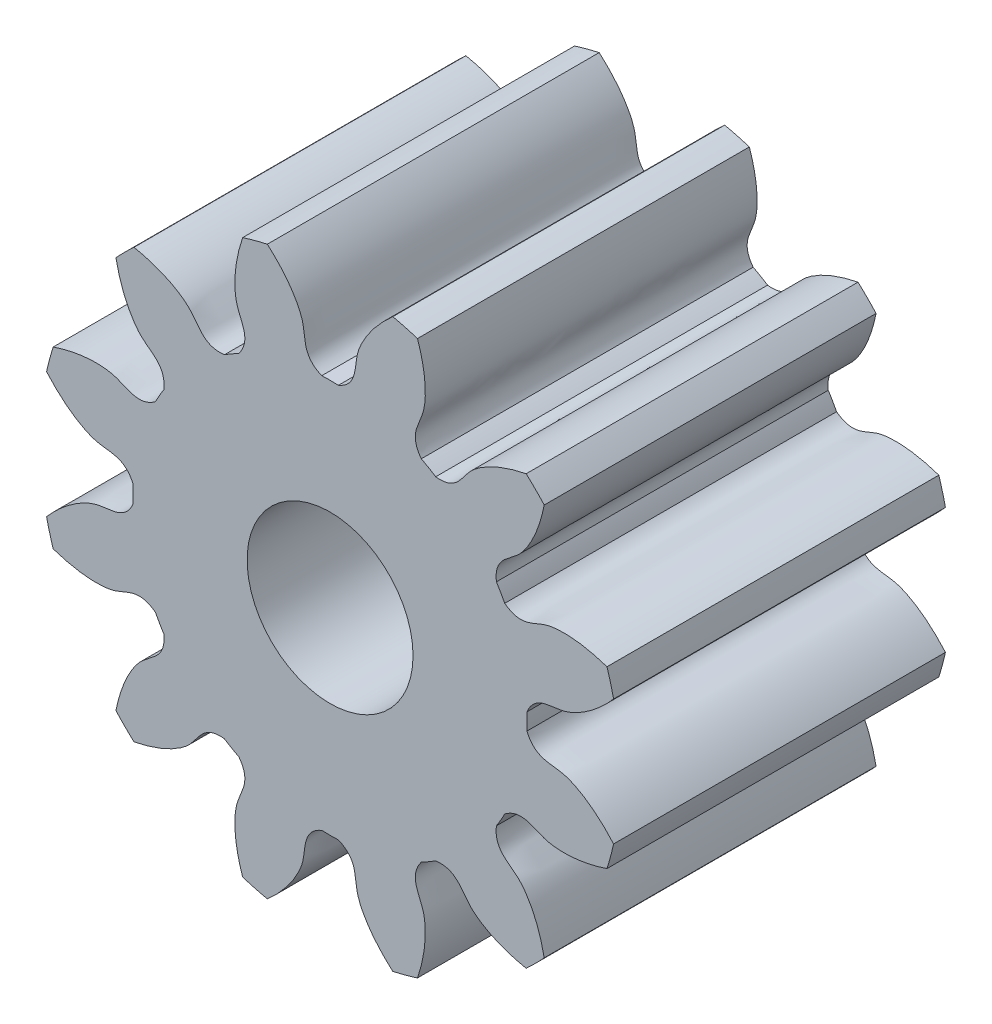
SolidWorks part; units mm, degrees
ref_plane "前视基准面" through (0, 0, 0) normal (0, 0, 1) x (1, 0, 0)
ref_plane "上视基准面" through (0, 0, 0) normal (0, 1, 0) x (1, 0, 0)
ref_plane "右视基准面" through (0, 0, 0) normal (1, 0, 0) x (0, 0, -1)
sketch "草图1" plane through (0, 0, 0) normal (0, 0, 1) x (1, 0, 0)
  arc A0 (-264.4461, -183.3216) -> (-265.0406, -183.4809) centre (-262.9333, -190.1562) ccw
  arc A1 (-262.7325, -185.4104) -> (-263.1342, -185.4104) centre (-262.9333, -190.1562) ccw
  arc A2 (-260.8261, -183.4809) -> (-261.4206, -183.3216) centre (-262.9333, -190.1562) ccw
  arc A3 (-260.3865, -186.1467) -> (-260.7344, -185.9458) centre (-262.9333, -190.1562) ccw
  arc A4 (-257.7708, -185.4288) -> (-258.206, -184.9936) centre (-262.9333, -190.1562) ccw
  arc A5 (-258.723, -187.9572) -> (-258.9238, -187.6094) centre (-262.9333, -190.1562) ccw
  arc A6 (-256.0987, -188.6434) -> (-256.258, -188.0489) centre (-262.9333, -190.1562) ccw
  arc A7 (-258.1876, -190.357) -> (-258.1876, -189.9553) centre (-262.9333, -190.1562) ccw
  arc A8 (-256.258, -192.2634) -> (-256.0987, -191.6689) centre (-262.9333, -190.1562) ccw
  arc A9 (-258.9238, -192.703) -> (-258.723, -192.3551) centre (-262.9333, -190.1562) ccw
  arc A10 (-258.206, -195.3187) -> (-257.7708, -194.8835) centre (-262.9333, -190.1562) ccw
  arc A11 (-260.7344, -194.3665) -> (-260.3865, -194.1657) centre (-262.9333, -190.1562) ccw
  arc A12 (-261.4206, -196.9908) -> (-260.8261, -196.8315) centre (-262.9333, -190.1562) ccw
  arc A13 (-263.1342, -194.9019) -> (-262.7325, -194.9019) centre (-262.9333, -190.1562) ccw
  arc A14 (-265.0406, -196.8315) -> (-264.4461, -196.9908) centre (-262.9333, -190.1562) ccw
  arc A15 (-265.4801, -194.1657) -> (-265.1323, -194.3665) centre (-262.9333, -190.1562) ccw
  arc A16 (-268.0959, -194.8835) -> (-267.6607, -195.3187) centre (-262.9333, -190.1562) ccw
  arc A17 (-267.1437, -192.3551) -> (-266.9429, -192.703) centre (-262.9333, -190.1562) ccw
  arc A18 (-269.7679, -191.6689) -> (-269.6086, -192.2634) centre (-262.9333, -190.1562) ccw
  arc A19 (-267.6791, -189.9553) -> (-267.6791, -190.357) centre (-262.9333, -190.1562) ccw
  arc A20 (-269.6086, -188.0489) -> (-269.7679, -188.6434) centre (-262.9333, -190.1562) ccw
  arc A21 (-266.9429, -187.6094) -> (-267.1437, -187.9572) centre (-262.9333, -190.1562) ccw
  arc A22 (-267.6607, -184.9936) -> (-268.0959, -185.4288) centre (-262.9333, -190.1562) ccw
  arc A23 (-265.1323, -185.9458) -> (-265.4801, -186.1467) centre (-262.9333, -190.1562) ccw
  circle A24 centre (-262.9333, -190.1562) radius 2
  spline S0 degree 3 poles (-265.1323, -185.9458) (-264.8184, -185.5296) (-265.1083, -185.2402) (-265.1944, -184.8832) (-265.2024, -184.8445) (-265.2113, -184.7911) (-265.2193, -184.7285) (-265.2255, -184.6566) (-265.2292, -184.5755) (-265.2298, -184.4852) (-265.2264, -184.386) (-265.2185, -184.2781) (-265.2052, -184.1615) (-265.1822, -184.0133) (-265.1444, -183.8306) (-265.0941, -183.6446) (-265.0562, -183.5266) (-265.0406, -183.4809) knots 0 0 0 0 0.218015 0.222044 0.231522 0.242897 0.256167 0.271332 0.288394 0.307351 0.328204 0.350953 0.375597 0.402137 0.445502 0.493132 0.523596 0.523596 0.523596 0.523596
  spline S1 degree 3 poles (-264.4461, -183.3216) (-264.3902, -183.3705) (-264.2991, -183.4545) (-264.1796, -183.5761) (-264.0856, -183.6797) (-264.0016, -183.78) (-263.9272, -183.8764) (-263.8619, -183.9684) (-263.8053, -184.0554) (-263.7568, -184.1367) (-263.7159, -184.2121) (-263.682, -184.2809) (-263.6546, -184.3427) (-263.6329, -184.3972) (-263.6186, -184.438) (-263.6095, -184.4667) (-263.5077, -184.8114) (-263.6141, -185.2069) (-263.1342, -185.4104) knots 0.476404 0.476404 0.476404 0.476404 0.523219 0.554498 0.583882 0.61137 0.636962 0.660659 0.682459 0.702364 0.720374 0.736487 0.750705 0.763028 0.773454 0.777956 0.781985 1 1 1 1
  spline S2 degree 3 poles (-262.7325, -185.4104) (-262.2525, -185.2069) (-262.359, -184.8114) (-262.2549, -184.4591) (-262.2426, -184.4216) (-262.2236, -184.3709) (-262.1992, -184.3127) (-262.1686, -184.2473) (-262.1312, -184.1752) (-262.0866, -184.0968) (-262.0341, -184.0125) (-261.9732, -183.923) (-261.9035, -183.8287) (-261.8095, -183.7118) (-261.6854, -183.5726) (-261.5488, -183.4366) (-261.457, -183.3534) (-261.4206, -183.3216) knots 0 0 0 0 0.218015 0.222044 0.231522 0.242897 0.256167 0.271332 0.288394 0.307351 0.328204 0.350953 0.375597 0.402137 0.445502 0.493132 0.523596 0.523596 0.523596 0.523596
  spline S3 degree 3 poles (-260.8261, -183.4809) (-260.8021, -183.5512) (-260.7653, -183.6695) (-260.7226, -183.8346) (-260.6929, -183.9712) (-260.6704, -184.1001) (-260.6541, -184.2208) (-260.6436, -184.3331) (-260.638, -184.4367) (-260.6367, -184.5315) (-260.639, -184.6172) (-260.6441, -184.6937) (-260.6512, -184.761) (-260.6597, -184.819) (-260.6677, -184.8615) (-260.6742, -184.8909) (-260.7583, -185.2402) (-261.0483, -185.5296) (-260.7344, -185.9458) knots 0.476404 0.476404 0.476404 0.476404 0.523219 0.554498 0.583882 0.61137 0.636962 0.660659 0.682459 0.702364 0.720374 0.736487 0.750705 0.763028 0.773454 0.777956 0.781985 1 1 1 1
  spline S4 degree 3 poles (-260.3865, -186.1467) (-259.8691, -186.2103) (-259.7635, -185.8146) (-259.4973, -185.5616) (-259.4679, -185.5353) (-259.4261, -185.5009) (-259.3758, -185.4627) (-259.3166, -185.4213) (-259.2482, -185.3775) (-259.1704, -185.3319) (-259.0828, -185.2852) (-258.9853, -185.2381) (-258.8777, -185.1914) (-258.7379, -185.1371) (-258.5608, -185.0786) (-258.3745, -185.0291) (-258.2534, -185.003) (-258.206, -184.9936) knots 0 0 0 0 0.218015 0.222044 0.231522 0.242897 0.256167 0.271332 0.288394 0.307351 0.328204 0.350953 0.375597 0.402137 0.445502 0.493132 0.523596 0.523596 0.523596 0.523596
  spline S5 degree 3 poles (-257.7708, -185.4288) (-257.7852, -185.5017) (-257.8124, -185.6226) (-257.8579, -185.7869) (-257.9006, -185.9201) (-257.9455, -186.043) (-257.9918, -186.1556) (-258.0388, -186.2581) (-258.0858, -186.3506) (-258.1321, -186.4333) (-258.1769, -186.5064) (-258.2195, -186.5702) (-258.2594, -186.6249) (-258.2957, -186.6709) (-258.3239, -186.7037) (-258.3442, -186.7259) (-258.5918, -186.9863) (-258.9875, -187.0919) (-258.9238, -187.6094) knots 0.476404 0.476404 0.476404 0.476404 0.523219 0.554498 0.583882 0.61137 0.636962 0.660659 0.682459 0.702364 0.720374 0.736487 0.750705 0.763028 0.773454 0.777956 0.781985 1 1 1 1
  spline S6 degree 3 poles (-258.723, -187.9572) (-258.3067, -188.2711) (-258.0174, -187.9812) (-257.6603, -187.8952) (-257.6217, -187.8871) (-257.5683, -187.8782) (-257.5056, -187.8703) (-257.4337, -187.8641) (-257.3526, -187.8603) (-257.2624, -187.8598) (-257.1632, -187.8631) (-257.0552, -187.8711) (-256.9387, -187.8843) (-256.7904, -187.9073) (-256.6078, -187.9451) (-256.4217, -187.9954) (-256.3038, -188.0334) (-256.258, -188.0489) knots 0 0 0 0 0.218015 0.222044 0.231522 0.242897 0.256167 0.271332 0.288394 0.307351 0.328204 0.350953 0.375597 0.402137 0.445502 0.493132 0.523596 0.523596 0.523596 0.523596
  spline S7 degree 3 poles (-256.0987, -188.6434) (-256.1476, -188.6993) (-256.2317, -188.7904) (-256.3533, -188.91) (-256.4568, -189.0039) (-256.5571, -189.0879) (-256.6536, -189.1623) (-256.7456, -189.2276) (-256.8325, -189.2842) (-256.9139, -189.3327) (-256.9892, -189.3736) (-257.058, -189.4075) (-257.1199, -189.435) (-257.1744, -189.4566) (-257.2152, -189.4709) (-257.2439, -189.48) (-257.5885, -189.5818) (-257.984, -189.4754) (-258.1876, -189.9553) knots 0.476404 0.476404 0.476404 0.476404 0.523219 0.554498 0.583882 0.61137 0.636962 0.660659 0.682459 0.702364 0.720374 0.736487 0.750705 0.763028 0.773454 0.777956 0.781985 1 1 1 1
  spline S8 degree 3 poles (-258.1876, -190.357) (-257.984, -190.837) (-257.5885, -190.7306) (-257.2363, -190.8346) (-257.1988, -190.8469) (-257.1481, -190.8659) (-257.0899, -190.8904) (-257.0245, -190.9209) (-256.9524, -190.9583) (-256.8739, -191.0029) (-256.7897, -191.0554) (-256.7002, -191.1163) (-256.6059, -191.186) (-256.489, -191.28) (-256.3497, -191.4041) (-256.2137, -191.5407) (-256.1306, -191.6325) (-256.0987, -191.6689) knots 0 0 0 0 0.218015 0.222044 0.231522 0.242897 0.256167 0.271332 0.288394 0.307351 0.328204 0.350953 0.375597 0.402137 0.445502 0.493132 0.523596 0.523596 0.523596 0.523596
  spline S9 degree 3 poles (-256.258, -192.2634) (-256.3283, -192.2874) (-256.4466, -192.3242) (-256.6117, -192.3669) (-256.7484, -192.3966) (-256.8773, -192.4191) (-256.998, -192.4354) (-257.1103, -192.4459) (-257.2139, -192.4515) (-257.3086, -192.4528) (-257.3943, -192.4505) (-257.4708, -192.4455) (-257.5381, -192.4383) (-257.5962, -192.4298) (-257.6387, -192.4218) (-257.668, -192.4154) (-258.0174, -192.3312) (-258.3067, -192.0413) (-258.723, -192.3551) knots 0.476404 0.476404 0.476404 0.476404 0.523219 0.554498 0.583882 0.61137 0.636962 0.660659 0.682459 0.702364 0.720374 0.736487 0.750705 0.763028 0.773454 0.777956 0.781985 1 1 1 1
  spline S10 degree 3 poles (-258.9238, -192.703) (-258.9875, -193.2204) (-258.5918, -193.326) (-258.3387, -193.5922) (-258.3124, -193.6216) (-258.278, -193.6634) (-258.2398, -193.7137) (-258.1985, -193.7729) (-258.1547, -193.8413) (-258.1091, -193.9192) (-258.0624, -194.0067) (-258.0153, -194.1042) (-257.9685, -194.2118) (-257.9143, -194.3516) (-257.8557, -194.5287) (-257.8063, -194.715) (-257.7801, -194.8361) (-257.7708, -194.8835) knots 0 0 0 0 0.218015 0.222044 0.231522 0.242897 0.256167 0.271332 0.288394 0.307351 0.328204 0.350953 0.375597 0.402137 0.445502 0.493132 0.523596 0.523596 0.523596 0.523596
  spline S11 degree 3 poles (-258.206, -195.3187) (-258.2788, -195.3044) (-258.3997, -195.2771) (-258.564, -195.2316) (-258.6972, -195.1889) (-258.8201, -195.144) (-258.9328, -195.0977) (-259.0353, -195.0507) (-259.1278, -195.0037) (-259.2105, -194.9574) (-259.2836, -194.9126) (-259.3473, -194.87) (-259.402, -194.8302) (-259.448, -194.7938) (-259.4808, -194.7656) (-259.503, -194.7453) (-259.7635, -194.4977) (-259.8691, -194.102) (-260.3865, -194.1657) knots 0.476404 0.476404 0.476404 0.476404 0.523219 0.554498 0.583882 0.61137 0.636962 0.660659 0.682459 0.702364 0.720374 0.736487 0.750705 0.763028 0.773454 0.777956 0.781985 1 1 1 1
  spline S12 degree 3 poles (-260.7344, -194.3665) (-261.0483, -194.7828) (-260.7583, -195.0721) (-260.6723, -195.4292) (-260.6643, -195.4678) (-260.6553, -195.5212) (-260.6474, -195.5839) (-260.6412, -195.6558) (-260.6375, -195.7369) (-260.6369, -195.8271) (-260.6402, -195.9263) (-260.6482, -196.0343) (-260.6615, -196.1508) (-260.6844, -196.2991) (-260.7223, -196.4817) (-260.7726, -196.6678) (-260.8105, -196.7857) (-260.8261, -196.8315) knots 0 0 0 0 0.218015 0.222044 0.231522 0.242897 0.256167 0.271332 0.288394 0.307351 0.328204 0.350953 0.375597 0.402137 0.445502 0.493132 0.523596 0.523596 0.523596 0.523596
  spline S13 degree 3 poles (-261.4206, -196.9908) (-261.4765, -196.9419) (-261.5676, -196.8578) (-261.6871, -196.7362) (-261.7811, -196.6327) (-261.8651, -196.5324) (-261.9395, -196.4359) (-262.0048, -196.3439) (-262.0614, -196.257) (-262.1099, -196.1756) (-262.1508, -196.1003) (-262.1847, -196.0315) (-262.2121, -195.9696) (-262.2338, -195.9151) (-262.2481, -195.8743) (-262.2572, -195.8457) (-262.359, -195.501) (-262.2525, -195.1055) (-262.7325, -194.9019) knots 0.476404 0.476404 0.476404 0.476404 0.523219 0.554498 0.583882 0.61137 0.636962 0.660659 0.682459 0.702364 0.720374 0.736487 0.750705 0.763028 0.773454 0.777956 0.781985 1 1 1 1
  spline S14 degree 3 poles (-263.1342, -194.9019) (-263.6141, -195.1055) (-263.5077, -195.501) (-263.6117, -195.8532) (-263.6241, -195.8907) (-263.643, -195.9414) (-263.6675, -195.9997) (-263.6981, -196.065) (-263.7354, -196.1372) (-263.78, -196.2156) (-263.8325, -196.2998) (-263.8934, -196.3893) (-263.9632, -196.4836) (-264.0572, -196.6005) (-264.1813, -196.7398) (-264.3179, -196.8758) (-264.4097, -196.959) (-264.4461, -196.9908) knots 0 0 0 0 0.218015 0.222044 0.231522 0.242897 0.256167 0.271332 0.288394 0.307351 0.328204 0.350953 0.375597 0.402137 0.445502 0.493132 0.523596 0.523596 0.523596 0.523596
  spline S15 degree 3 poles (-265.0406, -196.8315) (-265.0645, -196.7612) (-265.1014, -196.6429) (-265.1441, -196.4778) (-265.1737, -196.3411) (-265.1963, -196.2122) (-265.2125, -196.0915) (-265.2231, -195.9792) (-265.2286, -195.8756) (-265.2299, -195.7809) (-265.2277, -195.6952) (-265.2226, -195.6187) (-265.2155, -195.5514) (-265.2069, -195.4933) (-265.199, -195.4509) (-265.1925, -195.4215) (-265.1083, -195.0721) (-264.8184, -194.7828) (-265.1323, -194.3665) knots 0.476404 0.476404 0.476404 0.476404 0.523219 0.554498 0.583882 0.61137 0.636962 0.660659 0.682459 0.702364 0.720374 0.736487 0.750705 0.763028 0.773454 0.777956 0.781985 1 1 1 1
  spline S16 degree 3 poles (-265.4801, -194.1657) (-265.9976, -194.102) (-266.1032, -194.4977) (-266.3694, -194.7508) (-266.3988, -194.7771) (-266.4406, -194.8115) (-266.4909, -194.8497) (-266.5501, -194.891) (-266.6184, -194.9348) (-266.6963, -194.9804) (-266.7839, -195.0271) (-266.8814, -195.0742) (-266.989, -195.121) (-267.1288, -195.1752) (-267.3059, -195.2338) (-267.4922, -195.2833) (-267.6133, -195.3094) (-267.6607, -195.3187) knots 0 0 0 0 0.218015 0.222044 0.231522 0.242897 0.256167 0.271332 0.288394 0.307351 0.328204 0.350953 0.375597 0.402137 0.445502 0.493132 0.523596 0.523596 0.523596 0.523596
  spline S17 degree 3 poles (-268.0959, -194.8835) (-268.0815, -194.8107) (-268.0542, -194.6898) (-268.0087, -194.5255) (-267.966, -194.3923) (-267.9212, -194.2694) (-267.8748, -194.1567) (-267.8278, -194.0542) (-267.7808, -193.9617) (-267.7346, -193.879) (-267.6898, -193.8059) (-267.6472, -193.7422) (-267.6073, -193.6875) (-267.5709, -193.6415) (-267.5428, -193.6087) (-267.5225, -193.5865) (-267.2749, -193.326) (-266.8792, -193.2204) (-266.9429, -192.703) knots 0.476404 0.476404 0.476404 0.476404 0.523219 0.554498 0.583882 0.61137 0.636962 0.660659 0.682459 0.702364 0.720374 0.736487 0.750705 0.763028 0.773454 0.777956 0.781985 1 1 1 1
  spline S18 degree 3 poles (-267.1437, -192.3551) (-267.56, -192.0413) (-267.8493, -192.3312) (-268.2063, -192.4172) (-268.245, -192.4252) (-268.2984, -192.4342) (-268.361, -192.4421) (-268.4329, -192.4483) (-268.5141, -192.452) (-268.6043, -192.4526) (-268.7035, -192.4493) (-268.8115, -192.4413) (-268.928, -192.428) (-269.0762, -192.4051) (-269.2589, -192.3672) (-269.4449, -192.3169) (-269.5629, -192.279) (-269.6086, -192.2634) knots 0 0 0 0 0.218015 0.222044 0.231522 0.242897 0.256167 0.271332 0.288394 0.307351 0.328204 0.350953 0.375597 0.402137 0.445502 0.493132 0.523596 0.523596 0.523596 0.523596
  spline S19 degree 3 poles (-269.7679, -191.6689) (-269.719, -191.613) (-269.635, -191.522) (-269.5134, -191.4024) (-269.4098, -191.3084) (-269.3095, -191.2244) (-269.2131, -191.15) (-269.1211, -191.0847) (-269.0342, -191.0281) (-268.9528, -190.9796) (-268.8774, -190.9387) (-268.8086, -190.9048) (-268.7468, -190.8774) (-268.6923, -190.8558) (-268.6515, -190.8414) (-268.6228, -190.8323) (-268.2782, -190.7306) (-267.8826, -190.837) (-267.6791, -190.357) knots 0.476404 0.476404 0.476404 0.476404 0.523219 0.554498 0.583882 0.61137 0.636962 0.660659 0.682459 0.702364 0.720374 0.736487 0.750705 0.763028 0.773454 0.777956 0.781985 1 1 1 1
  spline S20 degree 3 poles (-267.6791, -189.9553) (-267.8826, -189.4754) (-268.2782, -189.5818) (-268.6304, -189.4778) (-268.6679, -189.4654) (-268.7186, -189.4465) (-268.7768, -189.422) (-268.8422, -189.3914) (-268.9143, -189.3541) (-268.9927, -189.3095) (-269.077, -189.257) (-269.1665, -189.1961) (-269.2608, -189.1263) (-269.3777, -189.0323) (-269.517, -188.9082) (-269.6529, -188.7716) (-269.7361, -188.6798) (-269.7679, -188.6434) knots 0 0 0 0 0.218015 0.222044 0.231522 0.242897 0.256167 0.271332 0.288394 0.307351 0.328204 0.350953 0.375597 0.402137 0.445502 0.493132 0.523596 0.523596 0.523596 0.523596
  spline S21 degree 3 poles (-269.6086, -188.0489) (-269.5383, -188.025) (-269.42, -187.9881) (-269.2549, -187.9454) (-269.1183, -187.9158) (-268.9894, -187.8932) (-268.8687, -187.877) (-268.7564, -187.8665) (-268.6528, -187.8609) (-268.558, -187.8596) (-268.4724, -187.8618) (-268.3958, -187.8669) (-268.3285, -187.874) (-268.2705, -187.8826) (-268.228, -187.8905) (-268.1986, -187.897) (-267.8493, -187.9812) (-267.56, -188.2711) (-267.1437, -187.9572) knots 0.476404 0.476404 0.476404 0.476404 0.523219 0.554498 0.583882 0.61137 0.636962 0.660659 0.682459 0.702364 0.720374 0.736487 0.750705 0.763028 0.773454 0.777956 0.781985 1 1 1 1
  spline S22 degree 3 poles (-266.9429, -187.6094) (-266.8792, -187.0919) (-267.2749, -186.9863) (-267.5279, -186.7202) (-267.5542, -186.6907) (-267.5886, -186.6489) (-267.6268, -186.5986) (-267.6682, -186.5394) (-267.712, -186.4711) (-267.7576, -186.3932) (-267.8043, -186.3056) (-267.8514, -186.2081) (-267.8981, -186.1006) (-267.9524, -185.9607) (-268.0109, -185.7836) (-268.0604, -185.5973) (-268.0865, -185.4762) (-268.0959, -185.4288) knots 0 0 0 0 0.218015 0.222044 0.231522 0.242897 0.256167 0.271332 0.288394 0.307351 0.328204 0.350953 0.375597 0.402137 0.445502 0.493132 0.523596 0.523596 0.523596 0.523596
  spline S23 degree 3 poles (-267.6607, -184.9936) (-267.5878, -185.008) (-267.467, -185.0353) (-267.3026, -185.0808) (-267.1694, -185.1235) (-267.0466, -185.1684) (-266.9339, -185.2147) (-266.8314, -185.2617) (-266.7389, -185.3087) (-266.6562, -185.3549) (-266.5831, -185.3997) (-266.5193, -185.4424) (-266.4646, -185.4822) (-266.4187, -185.5186) (-266.3858, -185.5467) (-266.3636, -185.567) (-266.1032, -185.8146) (-265.9976, -186.2103) (-265.4801, -186.1467) knots 0.476404 0.476404 0.476404 0.476404 0.523219 0.554498 0.583882 0.61137 0.636962 0.660659 0.682459 0.702364 0.720374 0.736487 0.750705 0.763028 0.773454 0.777956 0.781985 1 1 1 1
extrude "凸台-拉伸1" add sketch "草图1" along normal blind 8
